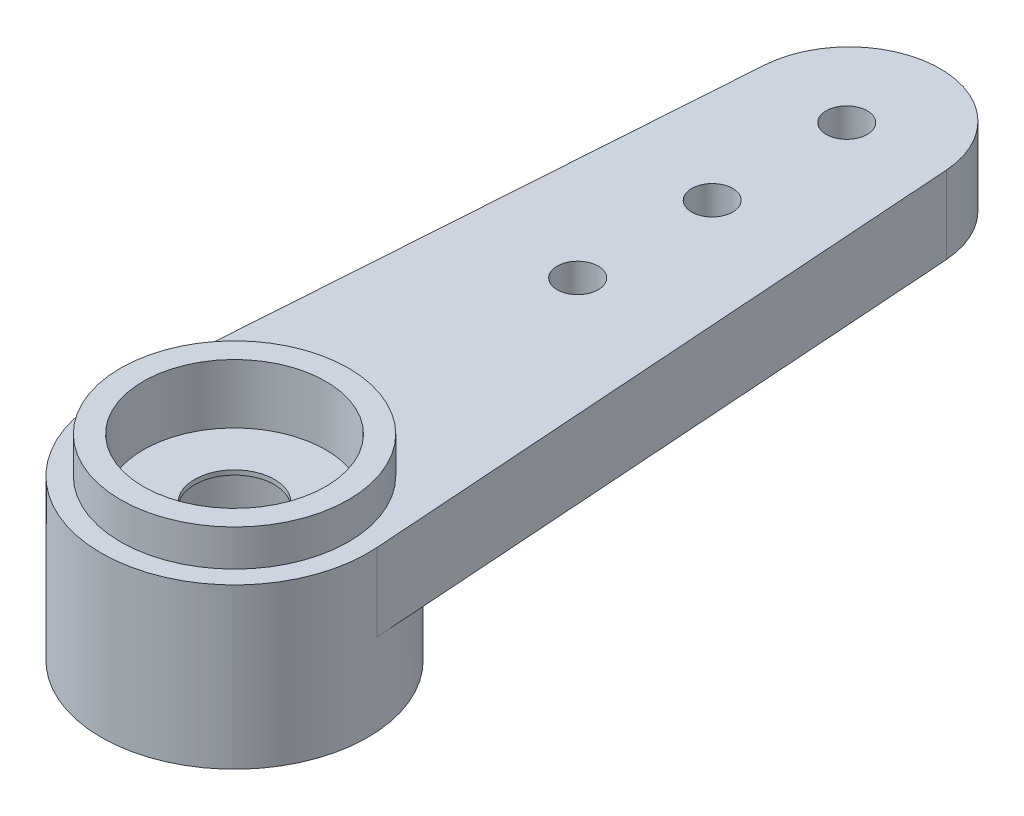
SolidWorks part; units mm, degrees
ref_plane "Front Plane" through (0, 0, 0) normal (0, 0, 1) x (1, 0, 0)
ref_plane "Top Plane" through (0, 0, 0) normal (0, 1, 0) x (1, 0, 0)
ref_plane "Right Plane" through (0, 0, 0) normal (1, 0, 0) x (0, 0, -1)
sketch "Sketch1" plane through (0, 0, 0) normal (0, 1, 0) x (1, 0, 0)
  circle A0 centre (0, 0) radius 2.925
  circle A1 centre (0, 0) radius 1.925
  dimension "D1" = 5.85
  dimension "D2" = 3.85
extrude "Boss-Extrude1" add sketch "Sketch1" along normal blind 1.8
sketch "Sketch3" plane through (0, 1.8, 0) normal (0, 1, 0) x (1, 0, 0)
  line L0 (0, 0) -> (0, 7.8393) construction
  line L1 (-1.9953, 13.6123) -> (-2.9181, 0.2008)
  line L2 (1.9953, 13.6123) -> (2.9181, 0.2008)
  circle A0 centre (0, 13.475) radius 2
  circle A1 centre (0, 0) radius 2.925 construction
  circle A2 centre (0, 0) radius 2.925
  dimension "D1" = 18.4
  dimension "D2" = 4
extrude "Boss-Extrude2" add sketch "Sketch3" along normal blind 1.7
sketch "Sketch4" plane through (0, 3.5, 0) normal (0, 1, 0) x (1, 0, 0)
  circle A0 centre (0, 0) radius 2
  circle A1 centre (0, 0) radius 2.5
  dimension "D1" = 5
  dimension "D2" = 4
extrude "Boss-Extrude3" add sketch "Sketch4" along normal blind 0.8
sketch "Sketch5" plane through (0, 3.5, 0) normal (0, 1, 0) x (1, 0, 0)
  line L0 (0, 0) -> (0, 15.475) construction
  arc A0 (1.9953, 13.6123) -> (-1.9953, 13.6123) centre (0, 13.475) ccw construction
  circle A1 centre (0, 13.425) radius 0.45
  circle A2 centre (0, 10.475) radius 0.45
  circle A3 centre (0, 7.525) radius 0.45
  dimension "D1" = 0.9
  dimension "D2" = 1.6
  dimension "D3" = 4.55
  dimension "D4" = 7.5
  dimension "D5" = 2.05
  dimension "D6" = 2.05
extrude "Cut-Extrude1" cut sketch "Sketch5" against normal through all
sketch "Sketch6" plane through (0, 3.5, 0) normal (0, 1, 0) x (1, 0, 0)
  circle A0 centre (0, 0) radius 0.875
  dimension "D1" = 1.75
extrude "Cut-Extrude2" cut sketch "Sketch6" against normal through all
sketch "Sketch7" plane through (0, 1.8, 0) normal (0, -1, 0) x (1, 0, 0)
  circle A0 centre (0, 0) radius 1.925 construction
  circle A1 centre (0, 0) radius 1.925
extrude "Cut-Extrude3" cut sketch "Sketch7" against normal blind 1.1
sketch "Sketch8" plane through (0, 3.5, 0) normal (0, 1, 0) x (1, 0, 0)
  circle A0 centre (0, 0) radius 2 construction
  circle A1 centre (0, 0) radius 2
extrude "Cut-Extrude4" cut sketch "Sketch8" against normal blind 0.5
